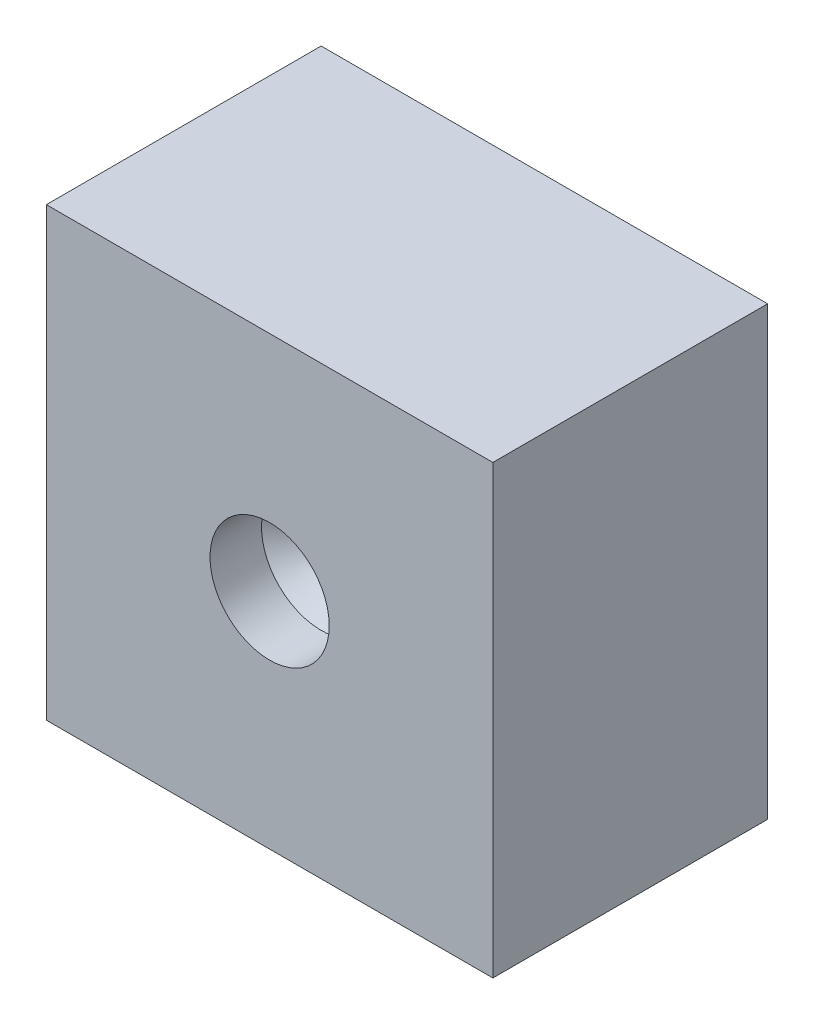
SolidWorks part; units mm, degrees
ref_plane "Ebene vorne" through (0, 0, 0) normal (1, 0, 0) x (0, 1, 0)
ref_plane "Ebene oben" through (0, 0, 0) normal (0, 0, 1) x (0, 1, 0)
ref_plane "Ebene rechts" through (0, 0, 0) normal (0, 1, 0) x (-1, 0, 0)
sketch "Skizze2" plane through (0, 0, 0) normal (0, 0, 1) x (0, 1, 0)
  line L1 (-13, -13) -> (13, -13)
  line L2 (-13, -13) -> (-13, 13)
  line L3 (-13, 13) -> (13, 13)
  line L4 (13, -13) -> (13, 13)
  line L5 (-13, -13) -> (13, 13) construction
  line L6 (-13, 13) -> (13, -13) construction
  point P0 (0, 0)
  dimension "D1" = 26
extrude "Aufsatz-Linear austragen1" add sketch "Skizze2" along normal blind 16
sketch "Skizze3" plane through (0, 0, 16) normal (0, 0, 1) x (1, 0, 0)
  point P0 (0, 0)
  point P3 (0, 0)
hole_wizard "Formsenkung für M3 Senkschraube mit Innensechskant1" positions "Skizze4" profile "Skizze5" countersink size "M3" standard "DIN" end condition through all
sketch "Skizze4" plane through (0, 0, 16) normal (0, 0, 1) x (1, 0, 0)
  point P0 (0, 0)
sketch "Skizze5" plane through (0, 0, 16) normal (1, 0, 0) x (0, -1, 0)
  line L0 (0, 0) -> (0, 16)
  line L1 (0, 16) -> (1.7, 16)
  line L2 (1.7, 16) -> (1.7, 4.77)
  line L3 (1.7, 4.77) -> (3.47, 3)
  line L4 (3.47, 3) -> (3.47, 0)
  line L6 (3.47, 0) -> (0, 0)
  line L7 (-1.7, 4.77) -> (-3.47, 3) construction
  line L11 (0, -6.35) -> (0, 107.95) construction
  dimension "Bohrerdurchmesser" = 3.4
  dimension "Bohrungstiefe" = 16
  dimension "Senkdurchmesser" = 6.94
  dimension "Senkwinkel" = 90
  dimension "Kopfspielraum" = 3
